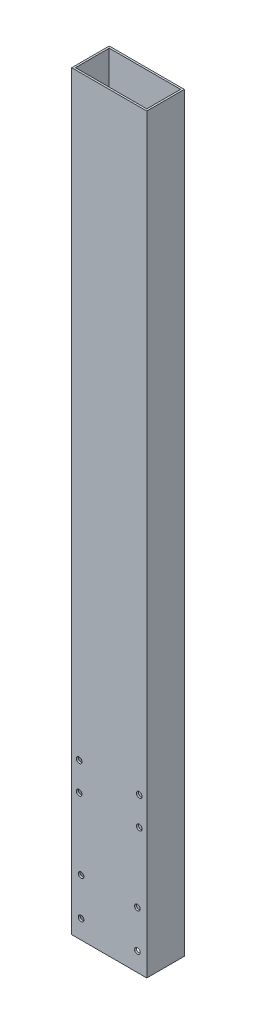
SolidWorks part; units mm, degrees
material "6061 合金"
ref_plane "前视基准面" through (0, 0, 0) normal (0, 0, 1) x (1, 0, 0)
ref_plane "上视基准面" through (0, 0, 0) normal (0, 1, 0) x (1, 0, 0)
ref_plane "右视基准面" through (0, 0, 0) normal (1, 0, 0) x (0, 0, -1)
sketch "草图1" plane through (0, 0, 0) normal (0, 0, 1) x (1, 0, 0)
  line L0 (0, 0) -> (0, -450)
  dimension "D1" = 450
other "20x40x1 LVGUAN20X40(1)"
ref_plane "基准面1" through (0, 0, 0) normal (0, -1, 0) x (1, 0, 0)
sketch "草图12" plane through (0, 0, 0) normal (0, -1, 0) x (1, 0, 0)
  line L1 (-20, 10) -> (20, 10)
  line L2 (-20, 10) -> (-20, -10)
  line L3 (-20, -10) -> (20, -10)
  line L4 (20, 10) -> (20, -10)
  line L5 (-20, 10) -> (20, -10) construction
  line L6 (-20, -10) -> (20, 10) construction
  line L7 (-19, 9) -> (19, 9)
  line L8 (-19, 9) -> (-19, -9)
  line L9 (-19, -9) -> (19, -9)
  line L10 (19, 9) -> (19, -9)
  line L11 (-19, 9) -> (19, -9) construction
  line L12 (-19, -9) -> (19, 9) construction
  point P0 (0, 0)
  point P5 (0, 0)
  point P11 (0, 0)
  dimension "D1" = 20
  dimension "D2" = 40
  dimension "D3" = 18
  dimension "D4" = 38
sketch "草图13" plane through (0, 0, 10) normal (0, 0, 1) x (1, 0, 0)
  circle A8 centre (16, -382.5) radius 1.5
  circle A9 centre (16, -367.5) radius 1.5
  circle A10 centre (-16, -367.5) radius 1.5
  circle A11 centre (-16, -382.5) radius 1.5
  circle A12 centre (15, -420) radius 1.5
  circle A13 centre (-15, -420) radius 1.5
  circle A14 centre (-15, -440) radius 1.5
  circle A15 centre (15, -440) radius 1.5
extrude "切除-拉伸1" cut sketch "草图13" against normal blind 51
sketch "草图14" plane through (0, 0, 0) normal (0, 1, 0) x (1, 0, 0)
  line L1 (-25.4644, -13.5183) -> (25.4644, -13.5183)
  line L2 (-25.4644, -13.5183) -> (-25.4644, 13.5183)
  line L3 (-25.4644, 13.5183) -> (25.4644, 13.5183)
  line L4 (25.4644, -13.5183) -> (25.4644, 13.5183)
  line L5 (-25.4644, -13.5183) -> (25.4644, 13.5183) construction
  line L6 (-25.4644, 13.5183) -> (25.4644, -13.5183) construction
  point P0 (0, 0)
extrude "切除-拉伸2" cut sketch "草图14" against normal blind 50
